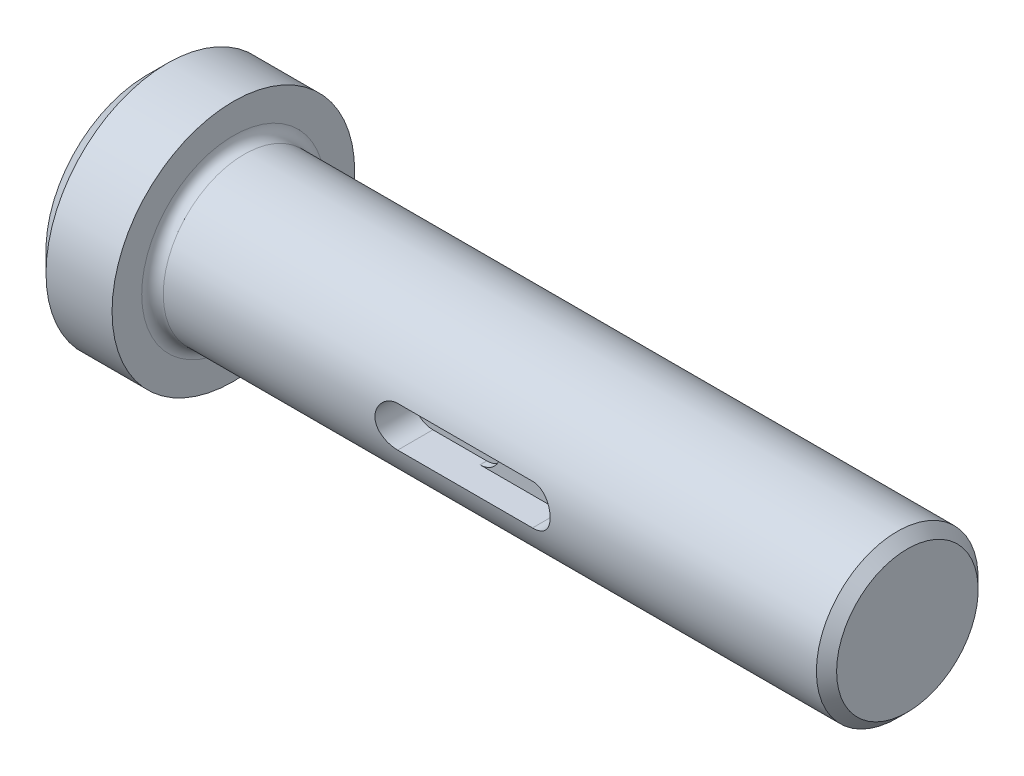
SolidWorks part; units mm, degrees
ref_plane "Front" through (0, 0, 0) normal (0, 0, 1) x (1, 0, 0)
ref_plane "Top" through (0, 0, 0) normal (0, 1, 0) x (1, 0, 0)
ref_plane "Right" through (0, 0, 0) normal (1, 0, 0) x (0, 0, -1)
sketch "Sketch2" plane through (0, 0, 0) normal (0, 0, 1) x (1, 0, 0)
  line L0 (-56.0675, 0) -> (68.4436, 0) construction
  line L1 (0, 0) -> (0, 9)
  line L2 (0, 9) -> (6.4, 9)
  line L3 (6.4, 9) -> (6.4, 6.8)
  line L4 (7.2, 6) -> (56.4, 6)
  line L5 (56.4, 6) -> (56.4, 0)
  line L6 (56.4, 0) -> (0, 0)
  arc A0 (7.2, 6) -> (6.4, 6.8) centre (7.2, 6.8) cw
  dimension "r" = 0.8
  dimension "d" = 12
  dimension "dk" = 18
  dimension "k" = 6.4
  dimension "l" = 50
revolve "Base" add sketch "Sketch2" angle 360 about L0
cosmetic thread "ThreadCosmetic1" [suppressed] parameters "b"=15, "D2"=10.106
chamfer "HeadChamfer" distance 1.5 angle 45 1 edges at (0, 0, 9)
ref_plane "Plane1" through (0, 0, 6) normal (0, 0, 1) x (1, 0, 0)
sketch "Sketch3" plane through (0, 0, 6) normal (0, 0, 1) x (1, 0, 0)
  line L0 (0, 0) -> (53.5043, 0) construction
  line L2 (24.4, 1.5) -> (34.4, 1.5)
  line L3 (34.4, -1.5) -> (24.4, -1.5)
  line L6 (6.4, -9) -> (6.4, 9) construction
  arc A0 (34.4, 1.5) -> (34.4, -1.5) centre (34.4, 0) cw
  arc A1 (24.4, -1.5) -> (24.4, 1.5) centre (24.4, 0) cw
  dimension "n" = 3
  dimension "l1" = 18
  dimension "l2" = 10
extrude "Cut-Extrude1" cut sketch "Sketch3" against normal blind 2.3
sketch "Sketch4" plane through (0, 0, 6) normal (0, 0, 1) x (1, 0, 0)
  line L4 (24.4, 1.5) -> (34.4, 1.5) construction
  line L5 (34.4, -1.5) -> (24.4, -1.5) construction
  line L6 (24.4, 1.5) -> (28.4, 1.5)
  line L7 (28.4, -1.5) -> (24.4, -1.5)
  arc A0 (28.4, -1.5) -> (28.4, 1.5) centre (28.4, 0) ccw
  arc A1 (24.4, 1.5) -> (24.4, -1.5) centre (24.4, 0) ccw construction
  arc A2 (24.4, 1.5) -> (24.4, -1.5) centre (24.4, 0) ccw
  dimension "l3" = 4
extrude "Cut-Extrude2" cut sketch "Sketch4" against normal blind 2.8
chamfer "BodyChamfer" distance 0.75 angle 45 1 edges at (56.4, 0, 6)
sketch "Sketch5" plane through (0, 0, 0) normal (0, 0, 1) x (1, 0, 0)
  line L0 (54.1917, 7.4583) -> (55.65, 7.4583)
  line L1 (55.65, 7.4583) -> (55.65, 6)
  line L2 (55.65, 6) -> (54.9208, 4.737)
  line L3 (54.9208, 4.737) -> (54.1917, 6)
  line L4 (54.1917, 6) -> (54.1917, 7.4583)
  line L6 (55.65, 6) -> (7.2, 6) construction
  line L7 (55.65, 6) -> (55.65, -6) construction
  dimension "D1" = 1.4583
revolve "Cut-Revolve10" [suppressed] cut sketch "Sketch5" angle 360 about axis through (-56.0675, 0, 0) along (1, 0, 0)
pattern_linear "LPattern10" [suppressed] count 8 along (1, 0, 0)
equation "\"D1@Plane1\" = \"d@Sketch2\" / 2"
equation "\"D1@BodyChamfer\" = \"c@HeadChamfer\" / 2"
equation "\"D1@Sketch5\" = \"pitch@LPattern10\" / 1.2"
equation "\"D1@LPattern10\" = ( \"b@ThreadCosmetic1\"  - \"D1@BodyChamfer\")/  \"pitch@LPattern10\""
